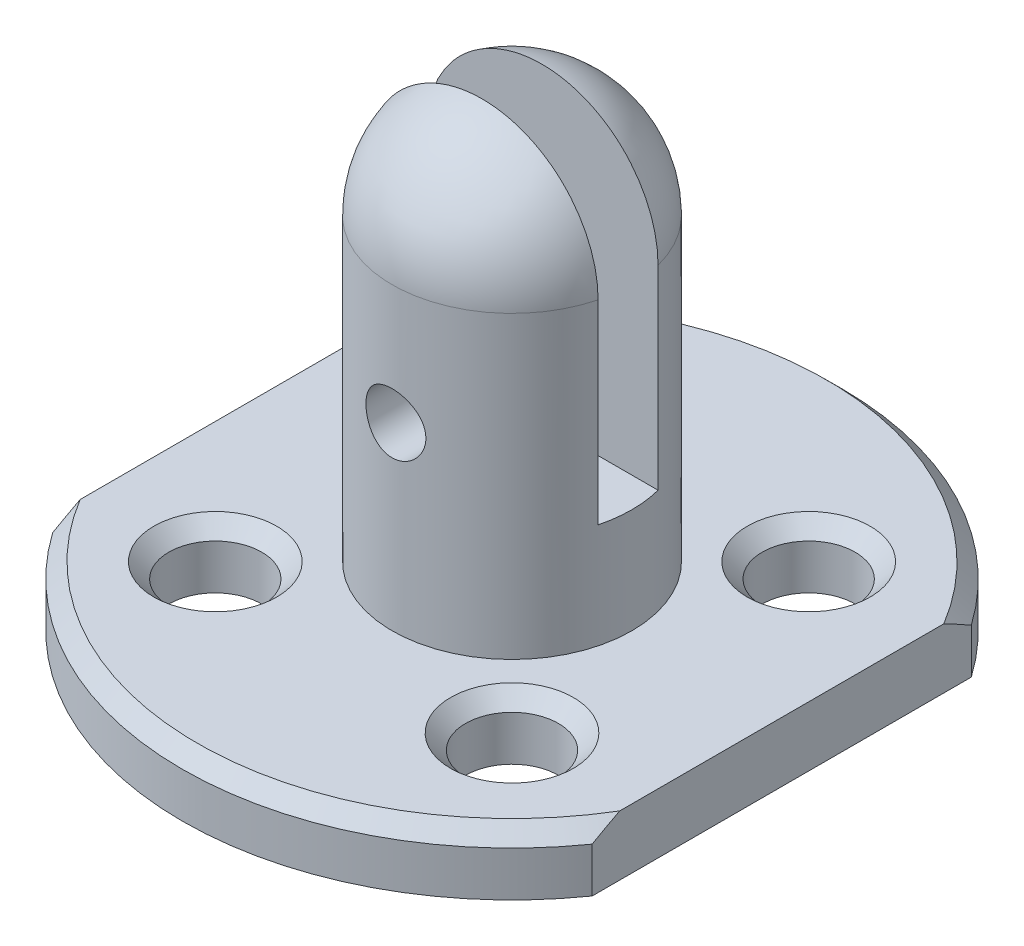
SolidWorks part; units mm, degrees
ref_plane "Front Plane" through (0, 0, 0) normal (0, 0, 1) x (1, 0, 0)
ref_plane "Top Plane" through (0, 0, 0) normal (0, 1, 0) x (1, 0, 0)
ref_plane "Right Plane" through (0, 0, 0) normal (1, 0, 0) x (0, 0, -1)
sketch "Sketch1" plane through (0, 0, 0) normal (0, 1, 0) x (1, 0, 0)
  line L2 (-9, -6.3246) -> (-9, 6.3246)
  line L4 (9, -6.3246) -> (9, 6.3246)
  arc A0 (9, 6.3246) -> (-9, 6.3246) centre (0, 0) ccw
  arc A1 (-9, -6.3246) -> (9, -6.3246) centre (0, 0) ccw
  dimension "D1" = 22
  dimension "D2" = 9
  dimension "D3" = 9
extrude "Boss-Extrude1" add sketch "Sketch1" along normal blind 2
sketch "Sketch2" plane through (0, 2, 0) normal (0, 1, 0) x (1, 0, 0)
  line L0 (0, 0) -> (0, 7) construction
  line L1 (0, 0) -> (4.9497, 4.9497) construction
  circle A0 centre (0, 0) radius 7 construction
  circle A1 centre (4.9497, 4.9497) radius 1.55
  circle A2 centre (4.9497, -4.9497) radius 1.55
  circle A3 centre (-4.9497, -4.9497) radius 1.55
  circle A4 centre (-4.9497, 4.9497) radius 1.55
  point P15 (0, 0)
  dimension "D1" = 14
  dimension "D3" = 3.1
  dimension "D2" = 45
  dimension "D4" = 4
extrude "Cut-Extrude1" cut sketch "Sketch2" against normal through all
chamfer "Chamfer1" distance 0.5 angle 45 6 edges at (4.9497, 2, 6.4997) (4.9497, 2, -3.3997) (-4.9497, 2, -3.3997) (-4.9497, 2, 6.4997) (0, 2, 11) (0, 2, -11)
sketch "Sketch3" plane through (0, 0, 0) normal (0, 0, 1) x (1, 0, 0)
  line L0 (9, 2) -> (-9, 2) construction
  line L1 (0, 2) -> (4, 2)
  line L2 (0, 2) -> (0, 16)
  line L3 (4, 2) -> (4, 12)
  arc A0 (4, 12) -> (0, 16) centre (0, 12) ccw
  dimension "D1" = 14
  dimension "D2" = 4
  dimension "D3" = 10
revolve "Revolve1" add sketch "Sketch3" angle 360 about L2
sketch "Sketch4" plane through (0, 0, 0) normal (1, 0, 0) x (0, 0, -1)
  line L1 (-1, 5.5) -> (1, 5.5)
  line L2 (-1, 5.5) -> (-1, 19.6338)
  line L3 (-1, 19.6338) -> (1, 19.6338)
  line L4 (1, 5.5) -> (1, 19.6338)
  line L5 (-1, 5.5) -> (1, 19.6338) construction
  line L6 (-1, 19.6338) -> (1, 5.5) construction
  line L7 (-5.4083, 2) -> (5.4083, 2) construction
  line L8 (-5.4083, 2) -> (5.4083, 2)
  point P0 (0, 12.5669)
  dimension "D1" = 2
  dimension "D2" = 3.5
  dimension "D3" = 14.1338
extrude "Cut-Extrude2" cut sketch "Sketch4" against normal mid plane 13 contours L1 L4 L3 L2
sketch "Sketch5" plane through (0, 0, 0) normal (0, 0, 1) x (1, 0, 0)
  circle A0 centre (0, 8) radius 1
  dimension "D1" = 2
  dimension "D2" = 8
extrude "Cut-Extrude3" cut sketch "Sketch5" against normal mid plane 13
sketch "Sketch6" plane through (0, 0, 0) normal (0, -1, 0) x (1, 0, 0)
  circle A0 centre (0, 0) radius 3
  dimension "D1" = 6
extrude "Boss-Extrude2" add sketch "Sketch6" along normal blind 1
